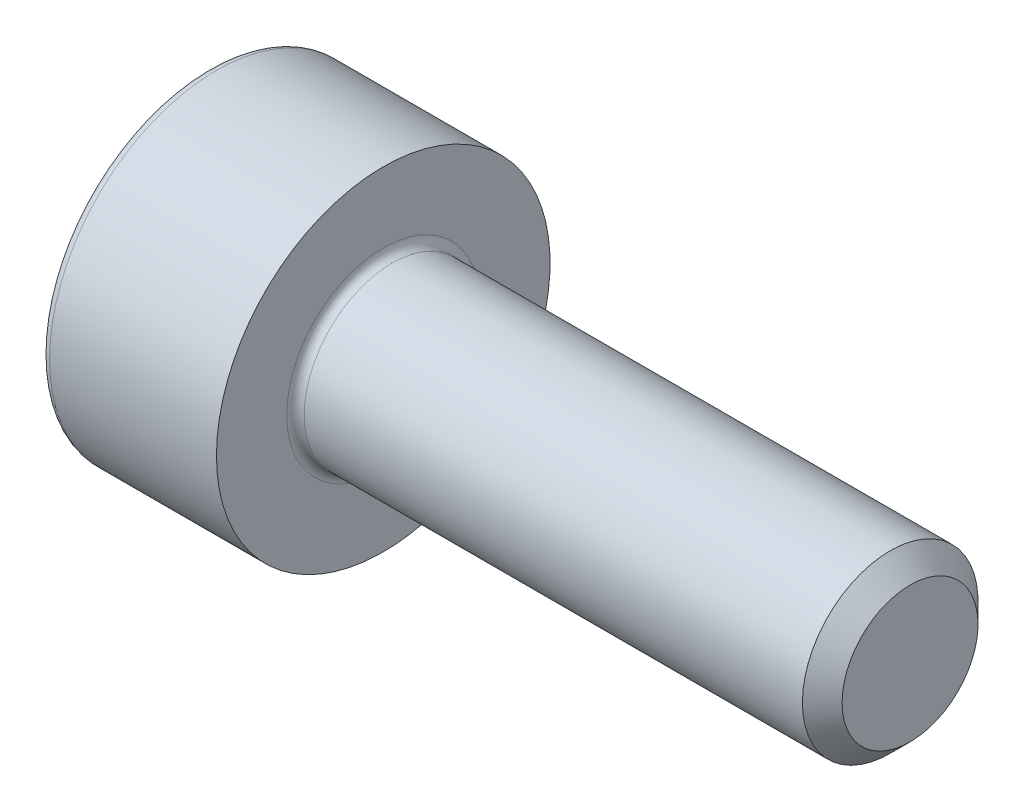
SolidWorks part; units mm, degrees
revolve "Base-Revolve" add sketch "BodySke"
sketch "BodySke" plane through (0, 0, 0) normal (0, 0, 1) x (1, 0, 0)
  line L0 (0, 0) -> (0, 1.9)
  line L1 (0, 1.9) -> (2, 1.9)
  line L2 (2, 1.9) -> (2, 1)
  line L3 (2, 1) -> (7.774, 1)
  line L4 (8, 0.774) -> (8, 0)
  line L5 (8, 0) -> (0, 0)
  line L6 (-31.75, 0) -> (127, 0) construction
  line L8 (8, 0.774) -> (7.774, 1)
  line L10 (8, -0.774) -> (7.774, -1) construction
  line L11 (2.4, 9.525) -> (2.4, 3.175) construction
  line L12 (2, 9.525) -> (2, 3.175) construction
  line L13 (-52, 9.525) -> (-52, 3.175) construction
  dimension "Head_ht" = 2
  dimension "Length" = 6
  dimension "Body_ch_ang" = 45
  dimension "Diameter" = 2
  dimension "Minor_dia" = 1.548
  dimension "Advance" = 0.4
  dimension "Thread_nom" = 6
  dimension "Thread_length" = 60
  dimension "Head_dia" = 3.8
cosmetic thread "ThreadCosmetic" [suppressed]
fillet "Fillet1" radius 0.1 1 edges at (2, 0, 1)
fillet "Fillet2" radius 0.1 1 edges at (0, 0, 1.9)
ref_plane "Plane1" through (0, 0, 0) normal (0, 0, 1) x (1, 0, 0)
ref_plane "Plane2" through (0, 0, 0) normal (0, 1, 0) x (1, 0, 0)
ref_plane "Plane3" through (0, 0, 0) normal (1, 0, 0) x (0, 0, -1)
other "Configuration Table"
sketch "Sketch2" plane through (0, 0, 0) normal (0, 0, 1) x (1, 0, 0)
  line L0 (0, 0.7725) -> (1, 0.7725)
  line L1 (1, 0.7725) -> (1.446, 0)
  line L2 (-31.75, 0) -> (127, 0) construction
  line L3 (1.446, 0) -> (0, 0)
  line L4 (0, 0) -> (0, 0.7725)
  line L6 (0, 0) -> (47.625, 0) construction
  dimension "D1" = 0.7725
  dimension "D2" = 60
  dimension "Depth" = 1
revolve "Hex-PreBroach" cut sketch "Sketch2" angle 360 about L6
sketch "Sketch3" plane through (0, 0, 0) normal (-1, 0, 0) x (0, 0.5, 0.866)
  line L0 (0.446, 0.7725) -> (-0.446, 0.7725)
  line L1 (-0.446, 0.7725) -> (-0.892, 0)
  line L2 (0.446, 0.7725) -> (0.892, 0)
  line L3 (0.446, -0.7725) -> (0.892, 0)
  line L4 (0.446, -0.7725) -> (-0.446, -0.7725)
  line L5 (-0.446, -0.7725) -> (-0.892, 0)
  dimension "D1" = 0.7725
  dimension "D2" = 0.7725
  dimension "Hex_size" = 1.545
extrude "Hex" cut sketch "Sketch3" against normal blind 1
sketch "ThdSchSke" plane through (0, 0, 0) normal (0, 0, 1) x (1, 0, 0)
  line L0 (3.2, -0.774) -> (3.0418, -1)
  line L1 (3.2, -0.774) -> (3.3582, -1)
  line L2 (3.3582, -1) -> (3.3582, -1.25)
  line L3 (-3.175, 0) -> (5.1513, 0) construction
  line L4 (0, 1.8) -> (0, -1.8) construction
  line L5 (3.3582, -1.25) -> (3.0418, -1.25)
  line L6 (3.0418, -1.25) -> (3.0418, -1)
  dimension "Thread_minor" = 1.548
  dimension "Diameter" = 2
  dimension "Start" = 3.2
revolve "ThreadSchematic" [suppressed] cut sketch "ThdSchSke" angle 360 about L3
pattern_linear "ThdSchPat" [suppressed]
equation "\"D2@Sketch3\" = \"Hex_size@Sketch3\" / 2"
equation "\"D1@Sketch3\" = \"Hex_size@Sketch3\" / 2"
equation "\"D1@Sketch2\" = \"Hex_size@Sketch3\" / 2"
equation "\"Thread_minor@ThreadCosmetic\"  =  \"Minor_dia@BodySke\""
equation "\"Depth@Sketch2\" =  \"Key_eng@Hex\""
equation "\"Thread_length@ThreadCosmetic\" = ((sgn( (\"Length@BodySke\" - \"Advance@BodySke\" * 3.0) - \"Thread_nom@BodySke\" )-1)*( (\"Length@BodySke\" - \"Advance@BodySke\" * 3.0) - \"Thread_nom@BodySke\" ))/-2+ \"Thread_nom@BodySke\""
equation "\"Thread_minor@ThdSchSke\" = \"Minor_dia@BodySke\""
equation "\"Diameter@ThdSchSke\" = \"Diameter@BodySke\""
equation "\"Overcut@ThdSchSke\" = \"Diameter@BodySke\" * 1.25"
equation "\"Start@ThdSchSke\" = \"Head_ht@BodySke\" + \"Length@BodySke\" - \"Thread_length@ThreadCosmetic\"  '---Non-countersunk---"
equation "\"Num_threads@ThdSchPat\" = int( \"Thread_length@ThreadCosmetic\" / \"Advance@BodySke\" + 0.999 )  + 1"
equation "\"Advance@ThdSchPat\" = \"Thread_length@ThreadCosmetic\" /  (\"Num_threads@ThdSchPat\" - 1) 'relax it"
equation "\"Num_threads@ThdSchPat\" = \"Num_threads@ThdSchPat\" - sgn( \"Num_threads@ThdSchPat\" - 1) '---chamfered tips only---"
